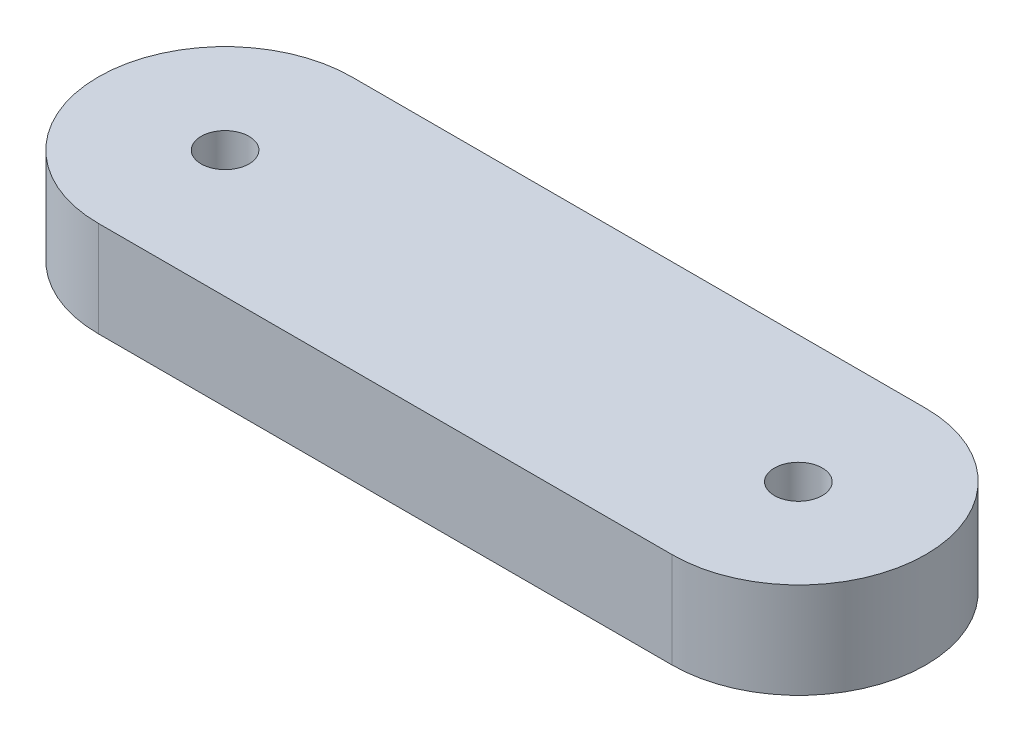
SolidWorks part; units mm, degrees
ref_plane "Спереди" through (0, 0, 0) normal (0, 0, 1) x (1, 0, 0)
ref_plane "Сверху" through (0, 0, 0) normal (0, 1, 0) x (1, 0, 0)
ref_plane "Справа" through (0, 0, 0) normal (1, 0, 0) x (0, 0, -1)
sketch "Эскиз1" plane through (0, 0, 0) normal (0, 1, 0) x (1, 0, 0)
  line L0 (-16.4089, 1.8552) -> (19.5911, 1.8549)
  line L1 (-16.4089, -14.0535) -> (19.5911, -14.0535)
  line L2 (-16.4089, 1.8552) -> (-16.4089, -14.0535) construction
  circle A0 centre (19.5911, -6.1355) radius 1.5019
  arc A1 (-16.4089, 1.8552) -> (-16.4089, -14.0535) centre (-16.4089, -6.0991) ccw
  circle A2 centre (-16.4089, -6.0991) radius 1.5019
  arc A3 (19.5911, -14.0535) -> (19.5911, 1.8549) centre (19.5911, -6.0993) ccw
  point P9 (0, 0)
  dimension "D1" = 36
  dimension "D2" = 36
  dimension "D3" = 36
extrude "Бобышка-Вытянуть1" add sketch "Эскиз1" along normal blind 6
